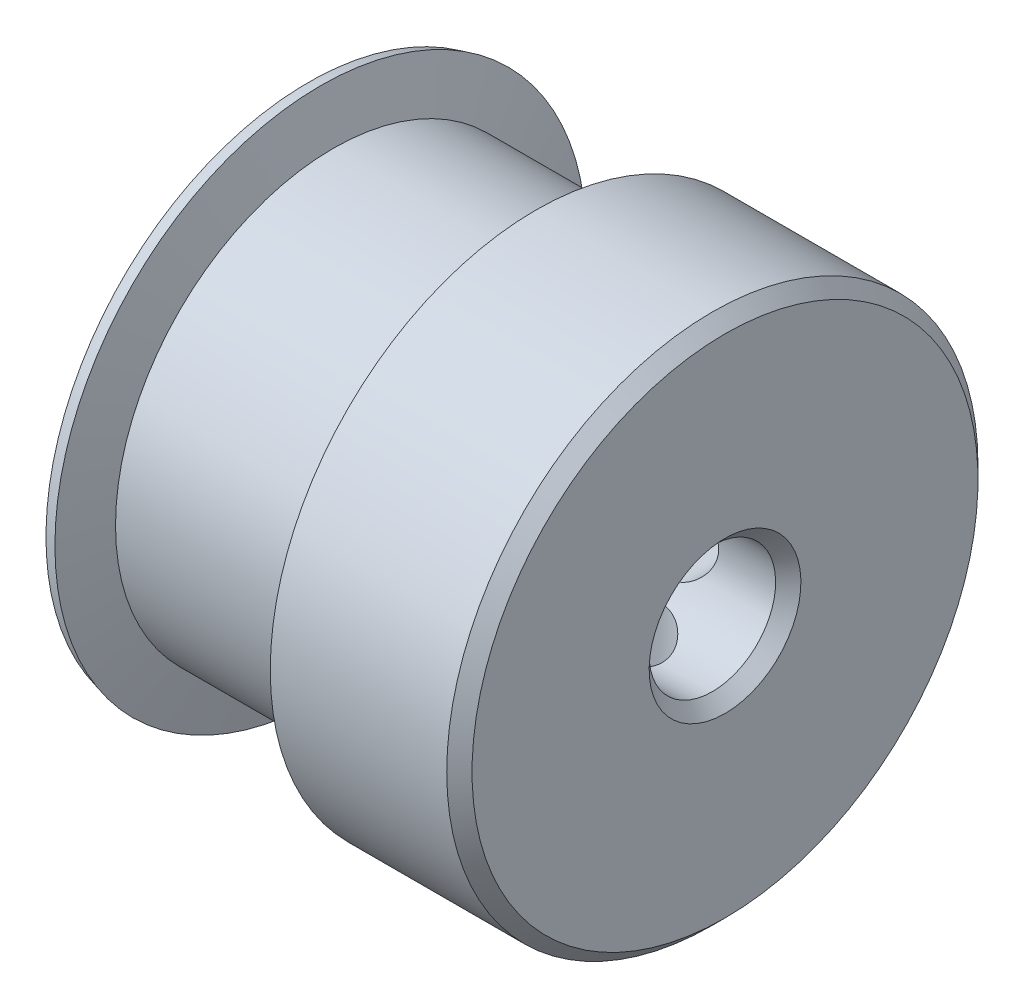
SolidWorks part; units mm, degrees
ref_plane "Piano frontale" through (0, 0, 0) normal (0, 0, 1) x (1, 0, 0)
ref_plane "Piano superiore" through (0, 0, 0) normal (0, 1, 0) x (1, 0, 0)
ref_plane "Piano destro" through (0, 0, 0) normal (1, 0, 0) x (0, 0, -1)
sketch "Schizzo1" plane through (0, 0, 0) normal (0, 0, 1) x (1, 0, 0)
  line L0 (-8, 0) -> (8, 0) construction
  line L1 (-8, 3) -> (-7.5, 2.5)
  line L2 (-7.5, 2.5) -> (7.5, 2.5)
  line L3 (7.5, 2.5) -> (8, 3)
  line L4 (8, 3) -> (8, 10)
  line L5 (8, 10) -> (7.5, 10.5)
  line L6 (7.5, 10.5) -> (0.5241, 10.5)
  line L7 (0.5241, 10.5) -> (0.0176, 8.61)
  line L8 (0.0176, 8.61) -> (-7.4824, 8.61)
  line L9 (-7.4824, 8.61) -> (-7.9888, 10.5)
  line L10 (-7.9888, 10.5) -> (-8.4717, 10.3706)
  line L11 (-8.4717, 10.3706) -> (-8, 8.61)
  line L12 (-8, 8.61) -> (-8, 3)
  point P3 (0, 0)
  dimension "D1" = 135
  dimension "D2" = 135
  dimension "D3" = 2.5
  dimension "D4" = 16
  dimension "D5" = 8
  dimension "D6" = 135
  dimension "D7" = 105
  dimension "D8" = 7.5
  dimension "D9" = 6.11
  dimension "D10" = 105
  dimension "D11" = 0.5
  dimension "D12" = 0.5
  dimension "D13" = 0.5
revolve "Rivoluzione1" add sketch "Schizzo1" angle 360 about L0
sketch "Schizzo2" plane through (0, 0, 0) normal (0, 0, 1) x (1, 0, 0)
  line L2 (0.5241, -10.5) -> (0.5241, 10.5) construction
  line L3 (7.5, -10.5) -> (7.5, 10.5) construction
  line L4 (0.5241, -10.5) -> (0.5241, 10.5) construction
  line L5 (7.5, -10.5) -> (7.5, 10.5) construction
  line L6 (0, 0) -> (7.5, 0) construction
  circle A0 centre (3.75, 0) radius 1.5
  dimension "D1" = 3
extrude "Taglio-Estrusione1" cut sketch "Schizzo2" against normal up to next
sketch "Schizzo3" plane through (0, 0, 0) normal (0, 1, 0) x (1, 0, 0)
  line L0 (0.5241, -10.5) -> (0.5241, 10.5) construction
  line L1 (7.5, -10.5) -> (7.5, 10.5) construction
  line L2 (0.5241, -10.5) -> (0.5241, 10.5) construction
  line L3 (7.5, -10.5) -> (7.5, 10.5) construction
  line L4 (0.5241, 0) -> (7.5, 0) construction
  circle A0 centre (4.012, 0) radius 1.5
  dimension "D1" = 3
extrude "Taglio-Estrusione2" cut sketch "Schizzo3" against normal up to next
